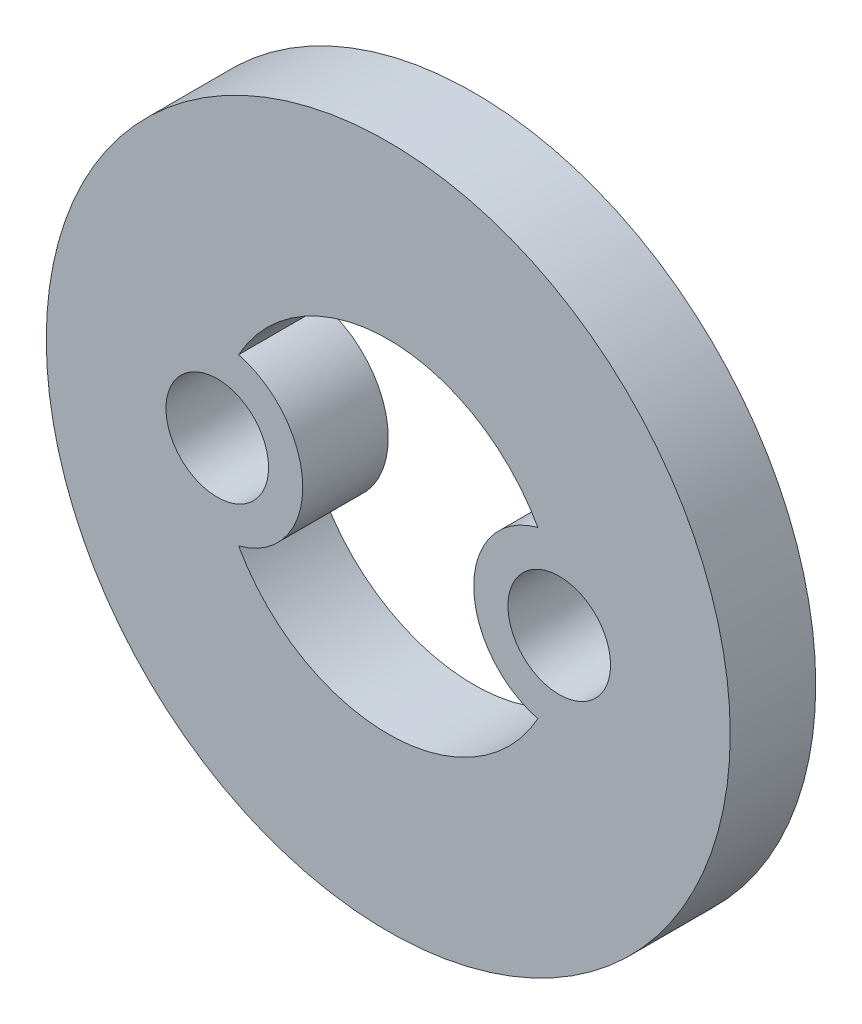
SolidWorks part; units mm, degrees
ref_plane "Alzado" through (0, 0, 0) normal (0, 0, 1) x (1, 0, 0)
ref_plane "Planta" through (0, 0, 0) normal (0, 1, 0) x (1, 0, 0)
ref_plane "Vista lateral" through (0, 0, 0) normal (1, 0, 0) x (0, 0, -1)
sketch "Croquis1" plane through (0, 0, 0) normal (0, 0, 1) x (1, 0, 0)
  circle A0 centre (10, 0) radius 3
  circle A1 centre (-10, 0) radius 3
  arc A2 (8.75, 4.8412) -> (-8.75, 4.8412) centre (0, 0) ccw
  circle A3 centre (0, 0) radius 20
  arc A4 (-8.75, -4.8412) -> (-8.75, 4.8412) centre (-10, 0) ccw
  arc A5 (8.75, 4.8412) -> (8.75, -4.8412) centre (10, 0) ccw
  arc A6 (-8.75, -4.8412) -> (8.75, -4.8412) centre (0, 0) ccw
  point P0 (0, 0)
  dimension "D3" = 20
  dimension "D5" = 6
  dimension "D6" = 6
  dimension "D7" = 10
  dimension "D8" = 10
  dimension "D9" = 40
  dimension "D4" = 10
extrude "Saliente-Extruir1" add sketch "Croquis1" along normal blind 5
